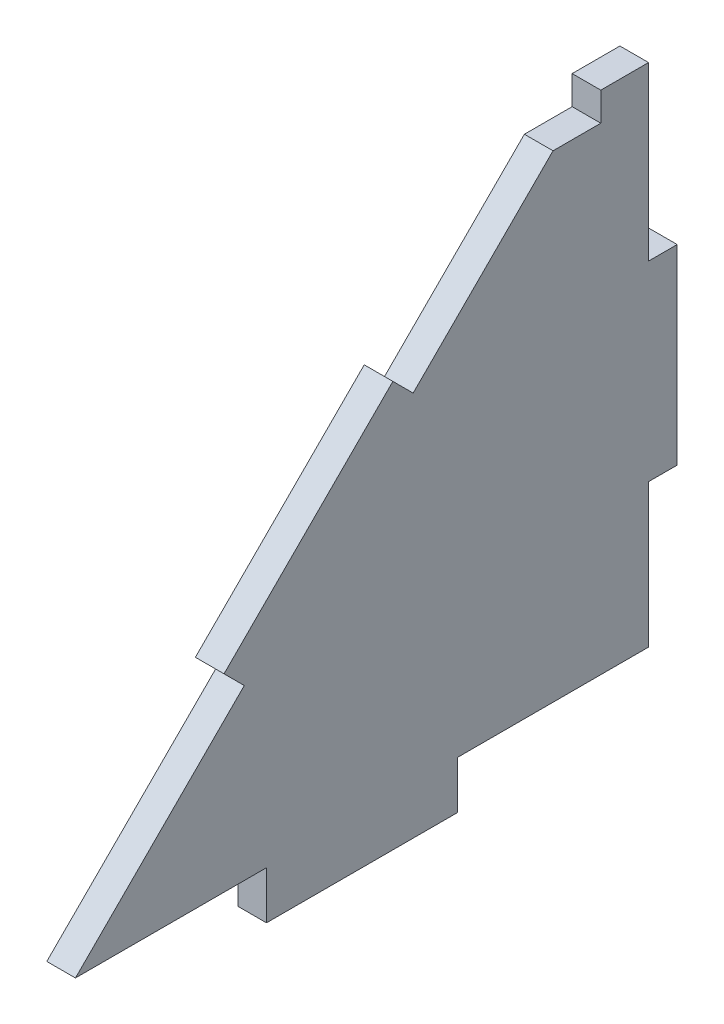
SolidWorks part; units mm, degrees
material "아크릴(내충격성)"
ref_plane "정면" through (0, 0, 0) normal (0, 0, 1) x (1, 0, 0)
ref_plane "윗면" through (0, 0, 0) normal (0, 1, 0) x (1, 0, 0)
ref_plane "우측면" through (0, 0, 0) normal (1, 0, 0) x (0, 0, -1)
sketch "스케치1" plane through (0, 0, 0) normal (1, 0, 0) x (0, 0, -1)
  line L0 (-50, -3) -> (51.8, -3) construction
  line L4 (51.8, 47) -> (51.8, 32)
  line L5 (-50, 50) -> (50, -50) construction
  line L6 (-50, -50) -> (50, 50) construction
  line L7 (0, -62.0295) -> (0, 60.7602) construction
  line L8 (9.4777, 14.6777) -> (7.3563, 16.799)
  line L14 (-8.2, -3) -> (11.8, -3)
  line L15 (11.8, -3) -> (11.8, -8)
  line L16 (31.8, -8) -> (31.8, -3)
  line L17 (31.8, -3) -> (51.8, -3)
  line L18 (11.8, -8) -> (31.8, -8)
  line L19 (7.3563, 16.799) -> (25.034, 34.4767)
  line L20 (25.034, 34.4767) -> (27.1553, 32.3553)
  line L22 (9.4777, 14.6777) -> (-8.2, -3)
  line L23 (51.8, 12) -> (51.8, -3)
  line L24 (-47, 47) -> (51.8, 47) construction
  line L25 (51.8, 32) -> (54.8, 32)
  line L28 (51.8, 12) -> (54.8, 12)
  line L29 (54.8, 32) -> (54.8, 12)
  line L31 (46.8, 47) -> (46.8, 50)
  line L32 (41.8, 47) -> (46.8, 47)
  line L33 (46.8, 50) -> (51.8, 50)
  line L35 (41.8, 47) -> (27.1553, 32.3553)
  line L36 (51.8, 50) -> (51.8, 47)
  point P0 (0, 0)
  dimension "D2" = 100
  dimension "D3" = 25
  dimension "D4" = 25
  dimension "D5" = 20.7107
  dimension "D6" = 3
  dimension "D7" = 20
  dimension "D8" = 20
  dimension "D9" = 3
  dimension "D10" = 15
  dimension "D11" = 20
  dimension "D12" = 60
  dimension "D13" = 10
  dimension "D14" = 50
extrude "보스-돌출1" add sketch "스케치1" along normal blind 3
